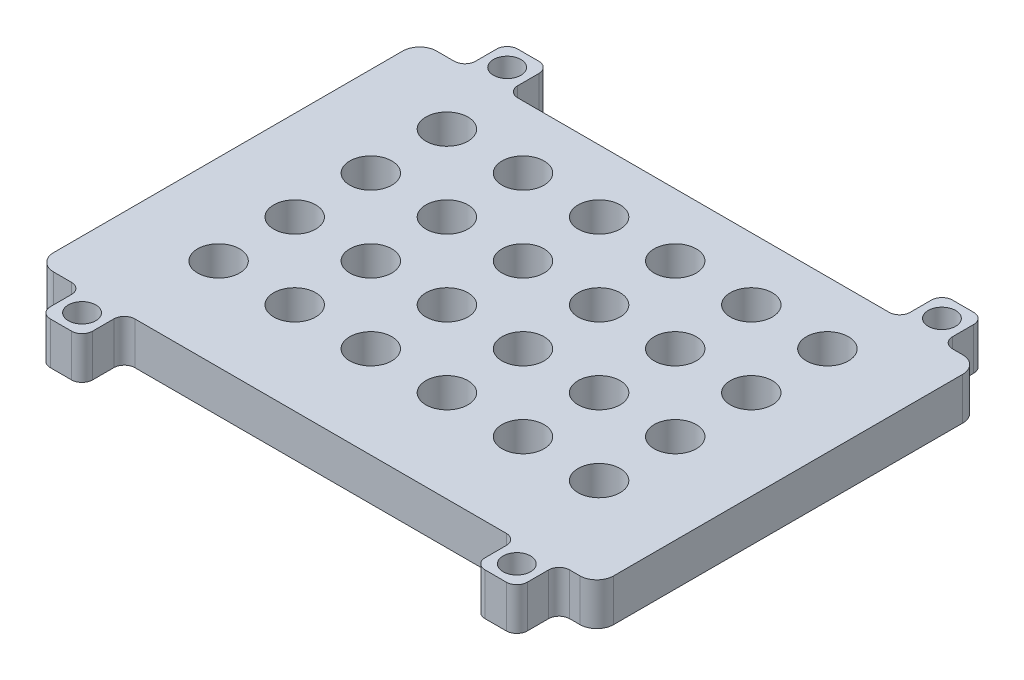
SolidWorks part; units mm, degrees
ref_plane "Front Plane" through (0, 0, 0) normal (0, 0, 1) x (1, 0, 0)
ref_plane "Top Plane" through (0, 0, 0) normal (0, 1, 0) x (1, 0, 0)
ref_plane "Right Plane" through (0, 0, 0) normal (1, 0, 0) x (0, 0, -1)
sketch "Sketch1" plane through (0, 0, 0) normal (0, 1, 0) x (1, 0, 0)
  line L1 (66.225, 45.2755) -> (-66.225, 45.2755)
  line L2 (66.225, 45.2755) -> (66.225, -45.2755)
  line L3 (66.225, -45.2755) -> (-66.225, -45.2755)
  line L4 (-66.225, 45.2755) -> (-66.225, -45.2755)
  line L5 (66.225, 45.2755) -> (-66.225, -45.2755) construction
  line L6 (66.225, -45.2755) -> (-66.225, 45.2755) construction
  line L8 (45, -23.5) -> (66.225, -23.5) construction
  line L9 (45, -23.5) -> (45, -45.2755) construction
  circle A0 centre (-45, 30.5) radius 3.5
  circle A1 centre (-27, 30.5) radius 3.5
  circle A2 centre (-9, 30.5) radius 3.5
  circle A3 centre (9, 30.5) radius 3.5
  circle A4 centre (27, 30.5) radius 3.5
  circle A5 centre (45, 30.5) radius 3.5
  circle A6 centre (-27, 12.5) radius 3.5
  circle A7 centre (-9, 12.5) radius 3.5
  circle A8 centre (9, 12.5) radius 3.5
  circle A9 centre (27, 12.5) radius 3.5
  circle A10 centre (45, 12.5) radius 3.5
  circle A11 centre (-27, -5.5) radius 3.5
  circle A12 centre (-9, -5.5) radius 3.5
  circle A13 centre (9, -5.5) radius 3.5
  circle A14 centre (27, -5.5) radius 3.5
  circle A15 centre (45, -5.5) radius 3.5
  circle A16 centre (-27, -23.5) radius 3.5
  circle A17 centre (-9, -23.5) radius 3.5
  circle A18 centre (9, -23.5) radius 3.5
  circle A19 centre (27, -23.5) radius 3.5
  circle A20 centre (45, -23.5) radius 3.5
  circle A21 centre (-45, 12.5) radius 3.5
  circle A22 centre (-45, -5.5) radius 3.5
  circle A23 centre (-45, -23.5) radius 3.5
  point P0 (0, 0)
  point P8 (0, 0)
  point P58 (0, 0)
  dimension "D3" = 7
  dimension "D4" = 6
  dimension "D1" = 132.45
  dimension "D2" = 90.551
  dimension "D6" = 18
  dimension "D7" = 18
  dimension "D8" = 21.7755
  dimension "D5" = 4
extrude "Boss-Extrude1" add sketch "Sketch1" along normal blind 10
sketch "Sketch3" plane through (0, 0, 0) normal (0, -1, 0) x (1, 0, 0)
  line L0 (66.225, -45.2755) -> (-66.225, -45.2755) construction
  line L1 (47.3134, -45.2755) -> (57.3134, -45.2755)
  line L2 (47.3134, -45.2755) -> (47.3134, -55.2755)
  line L3 (47.3134, -55.2755) -> (57.3134, -55.2755)
  line L4 (57.3134, -45.2755) -> (57.3134, -55.2755)
  line L5 (-66.225, 45.2755) -> (66.225, 45.2755) construction
  line L6 (-45.5226, -45.2755) -> (-55.5226, -45.2755)
  line L7 (-45.5226, -45.2755) -> (-45.5226, -55.2755)
  line L8 (-45.5226, -55.2755) -> (-55.5226, -55.2755)
  line L9 (-55.5226, -45.2755) -> (-55.5226, -55.2755)
  line L10 (-55.5226, 45.2755) -> (-45.5226, 45.2755)
  line L11 (-55.5226, 45.2755) -> (-55.5226, 55.2755)
  line L12 (-55.5226, 55.2755) -> (-45.5226, 55.2755)
  line L13 (-45.5226, 45.2755) -> (-45.5226, 55.2755)
  line L14 (-55.5226, -45.2755) -> (-66.225, -45.2755) construction
  line L15 (47.3134, 45.2755) -> (57.3134, 45.2755)
  line L16 (47.3134, 45.2755) -> (47.3134, 55.2755)
  line L17 (47.3134, 55.2755) -> (57.3134, 55.2755)
  line L18 (57.3134, 45.2755) -> (57.3134, 55.2755)
  line L21 (-55.5226, 45.2755) -> (-66.225, 45.2755) construction
  line L22 (47.3134, 55.2755) -> (57.3134, 45.2755) construction
  line L23 (47.3134, -55.2755) -> (57.3134, -45.2755) construction
  point P24 (45, 23.5)
  point P29 (52.3134, 50.2755)
  point P31 (52.3134, -50.2755)
  dimension "D1" = 10
  dimension "D2" = 92.836
  dimension "D3" = 92.836
  dimension "D4" = 7.3134
  dimension "D5" = 7.3134
extrude "Boss-Extrude3" add sketch "Sketch3" against normal up to surface (10 mm away) up to face at (-45, 10, 9)
sketch "Sketch4" plane through (0, 0, 0) normal (0, -1, 0) x (-1, 0, 0)
  line L0 (-57.3134, 55.2755) -> (-47.3134, 45.2755) construction
  line L1 (55.5226, 55.2755) -> (45.5226, 45.2755) construction
  line L2 (-57.3134, -45.2755) -> (-47.3134, -55.2755) construction
  line L3 (55.5226, -45.2755) -> (45.5226, -55.2755) construction
  circle A0 centre (-52.3134, -50.2755) radius 3.25
  circle A1 centre (50.5226, -50.2755) radius 3.25
  circle A2 centre (50.5226, 50.2755) radius 3.25
  circle A3 centre (-52.3134, 50.2755) radius 3.25
  dimension "D1" = 6.5
extrude "Cut-Extrude2" cut sketch "Sketch4" against normal through all
fillet "Fillet2" radius 2.5 16 edges at (47.3134, 5, 55.2755) (47.3134, 5, 45.2755) (57.3134, 5, 55.2755) (57.3134, 5, 45.2755) (-45.5226, 5, 55.2755) (-55.5226, 5, 55.2755) (-45.5226, 5, -45.2755) (-45.5226, 5, -55.2755) (-55.5226, 5, -45.2755) (-55.5226, 5, -55.2755) (47.3134, 5, -55.2755) (57.3134, 5, -55.2755)
fillet "Fillet3" radius 4 4 edges at (-66.225, 5, -45.2755) (-66.225, 5, 45.2755) (66.225, 5, 45.2755) (66.225, 5, -45.2755)
sketch "Sketch5" plane through (0, 10, 0) normal (0, 1, 0) x (1, 0, 0)
  circle A0 centre (45, -23.5) radius 4.975
  circle A1 centre (27, -23.5) radius 4.975
  circle A2 centre (9, -23.5) radius 4.975
  circle A3 centre (-9, -23.5) radius 4.975
  circle A4 centre (-27, -23.5) radius 4.975
  circle A5 centre (-45, -23.5) radius 4.975
  circle A6 centre (45, -5.5) radius 4.975
  circle A7 centre (27, -5.5) radius 4.975
  circle A8 centre (9, -5.5) radius 4.975
  circle A9 centre (-9, -5.5) radius 4.975
  circle A10 centre (-27, -5.5) radius 4.975
  circle A11 centre (-45, -5.5) radius 4.975
  circle A12 centre (45, 12.5) radius 4.975
  circle A13 centre (27, 12.5) radius 4.975
  circle A14 centre (9, 12.5) radius 4.975
  circle A15 centre (-9, 12.5) radius 4.975
  circle A16 centre (-27, 12.5) radius 4.975
  circle A17 centre (-45, 12.5) radius 4.975
  circle A18 centre (45, 30.5) radius 4.975
  circle A19 centre (27, 30.5) radius 4.975
  circle A20 centre (9, 30.5) radius 4.975
  circle A21 centre (-9, 30.5) radius 4.975
  circle A22 centre (-27, 30.5) radius 4.975
  circle A23 centre (-45, 30.5) radius 4.975
  dimension "D1" = 9.95
extrude "Cut-Extrude3" cut sketch "Sketch5" against normal blind 9.5
